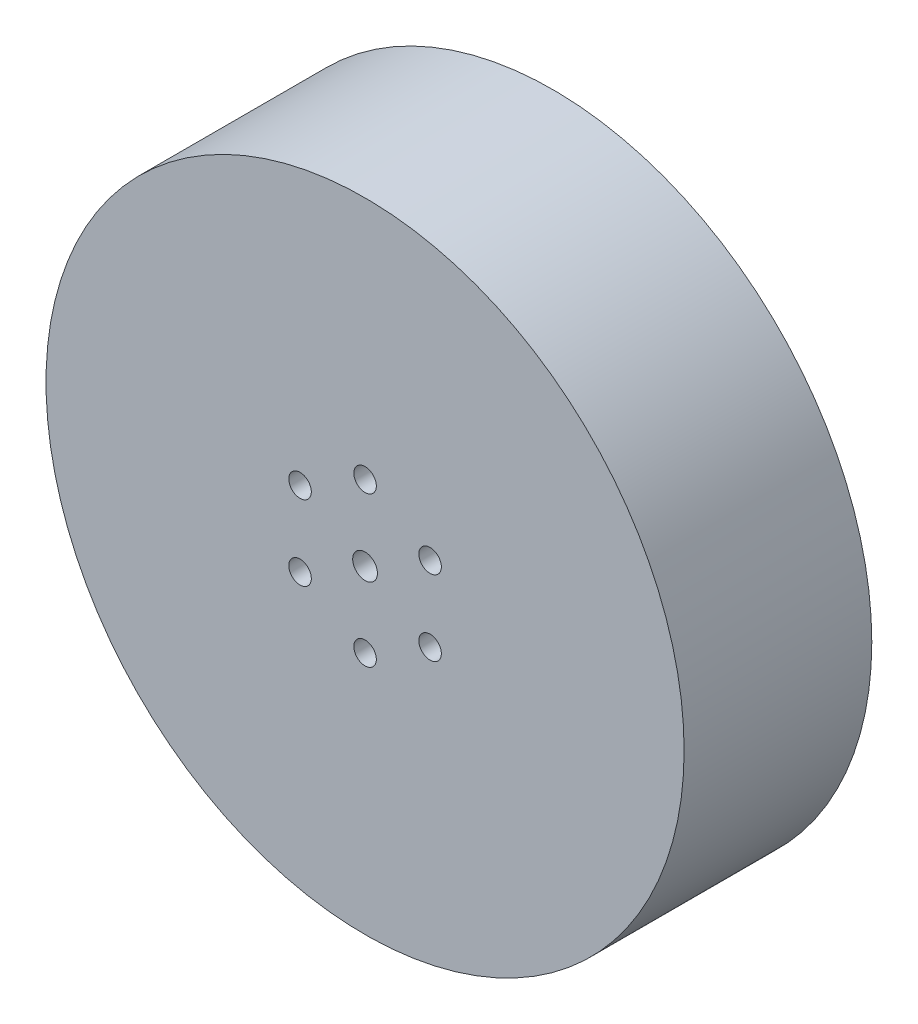
SolidWorks part; units mm, degrees
ref_plane "前视基准面" through (0, 0, 0) normal (0, 0, 1) x (1, 0, 0)
ref_plane "上视基准面" through (0, 0, 0) normal (0, 1, 0) x (1, 0, 0)
ref_plane "右视基准面" through (0, 0, 0) normal (1, 0, 0) x (0, 0, -1)
sketch "Sketch1" plane through (0, 0, 0) normal (0, 0, 1) x (1, 0, 0)
  circle A0 centre (0, 0) radius 42.5
  circle A1 centre (0, 0) radius 14
  circle A2 centre (0, 0) radius 10 construction
  circle A3 centre (0, 10) radius 1.5
  circle A4 centre (8.6603, 5) radius 1.5
  circle A5 centre (8.6603, -5) radius 1.5
  circle A6 centre (0, -10) radius 1.5
  circle A7 centre (-8.6603, -5) radius 1.5
  circle A8 centre (-8.6603, 5) radius 1.5
  point P19 (0, 0)
  dimension "D1" = 28
  dimension "D2" = 20
  dimension "D3" = 6
  dimension "D4" = 85
extrude "Boss-Extrude1" add sketch "Sketch1" along normal blind 25 contours A0 A1 | A1 A8 A7 A6 A5 A4 A3
sketch "Sketch2" plane through (0, 0, 0) normal (0, 0, -1) x (-1, 0, 0)
  circle A0 centre (0, 0) radius 14
  circle A1 centre (0, 10) radius 1.5
  circle A2 centre (8.6603, 5) radius 1.5
  circle A3 centre (8.6603, -5) radius 1.5
  circle A4 centre (0, -10) radius 1.5
  circle A5 centre (-8.6603, -5) radius 1.5
  circle A6 centre (-8.6603, 5) radius 1.5
  point P18 (0, 0)
  dimension "D1" = 6
extrude "Boss-Extrude2" add sketch "Sketch2" along normal blind 2
sketch "Sketch3" plane through (0, 0, 25) normal (0, 0, 1) x (1, 0, 0)
  circle A0 centre (0, 0) radius 2
hole_wizard "M4 Tapped Hole1" positions "3DSketch1" profile "Sketch4" tap size "M4" standard "GB"
sketch3d "3DSketch1"
  point P0 (0, 0, 25)
sketch "Sketch4" plane through (0, 0, 25) normal (1, 0, 0) x (0, -1, 0)
  line L0 (0, 0) -> (0, 5.9914)
  line L1 (0, 5.9914) -> (1.65, 5)
  line L2 (1.65, 5) -> (1.65, 0)
  line L5 (1.65, 0) -> (0, 0)
  line L10 (0, 5.9914) -> (-1.65, 5) construction
  line L11 (0, -6.35) -> (0, 107.95) construction
  dimension "Tap Drill Dia." = 3.3
  dimension "Tap Drill Depth" = 5
  dimension "Drill Angle" = 118
cosmetic thread "Hole Thread1" parameters "D1"=5, "D2"=4
